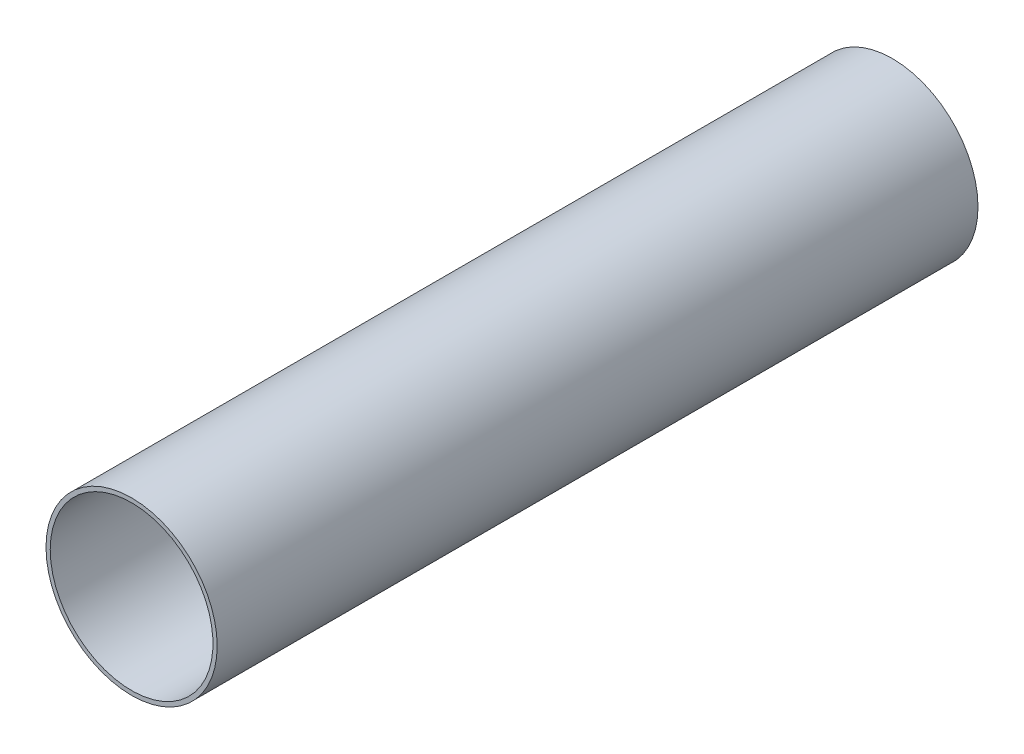
SolidWorks part; units mm, degrees
ref_plane "Front Plane" through (0, 0, 0) normal (0, 0, 1) x (1, 0, 0)
ref_plane "Top Plane" through (0, 0, 0) normal (0, 1, 0) x (1, 0, 0)
ref_plane "Right Plane" through (0, 0, 0) normal (1, 0, 0) x (0, 0, -1)
sketch "Sketch1" plane through (0, 0, 0) normal (0, 0, 1) x (1, 0, 0)
  circle A0 centre (0, 0) radius 20.25
  circle A1 centre (0, 0) radius 19.25
  dimension "D1" = 38.5
  dimension "D2" = 40.5
extrude "Boss-Extrude1" add sketch "Sketch1" along normal blind 180
